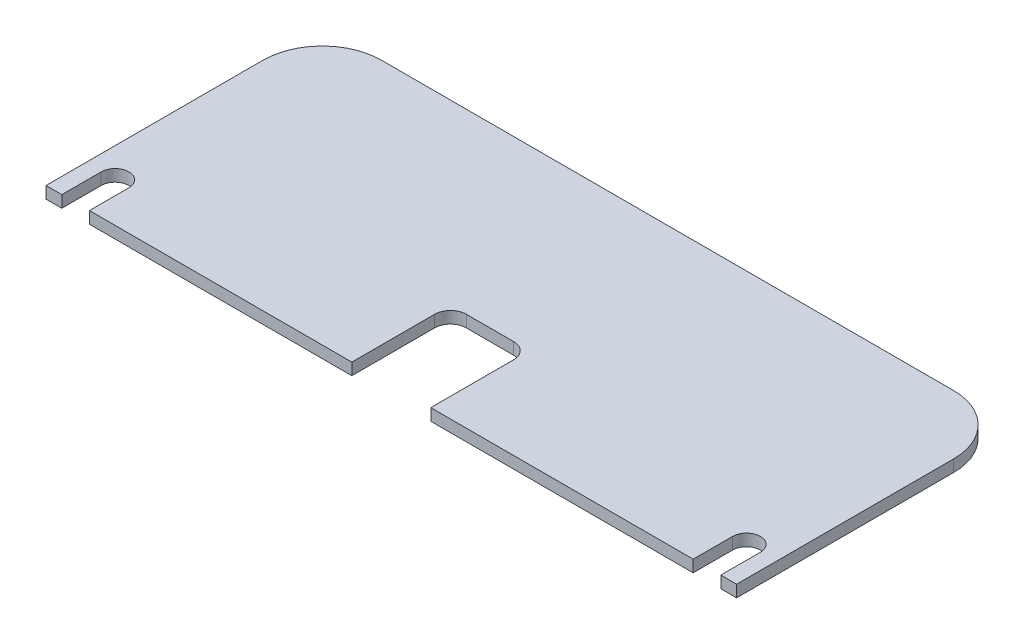
SolidWorks part; units mm, degrees
ref_plane "Front Plane" through (0, 0, 0) normal (0, 0, 1) x (1, 0, 0)
ref_plane "Top Plane" through (0, 0, 0) normal (0, 1, 0) x (1, 0, 0)
ref_plane "Right Plane" through (0, 0, 0) normal (1, 0, 0) x (0, 0, -1)
sketch "Sketch1" plane through (0, 0, 0) normal (0, 1, 0) x (1, 0, 0)
  line L1 (0, 0) -> (175, 0)
  line L2 (0, 0) -> (0, 70)
  line L3 (0, 70) -> (175, 70)
  line L4 (175, 0) -> (175, 70)
  dimension "D1" = 175
  dimension "D2" = 70
extrude "Boss-Extrude1" add sketch "Sketch1" along normal blind 3
sketch "Sketch2" plane through (0, 3, 0) normal (0, 1, 0) x (1, 0, 0)
  line L0 (87.5, 70) -> (87.5, 0) construction
  line L1 (77.5, 25) -> (97.5, 25)
  line L2 (77.5, 25) -> (77.5, 0)
  line L3 (77.5, 0) -> (97.5, 0)
  line L4 (97.5, 25) -> (97.5, 0)
  line L5 (0, 0) -> (175, 0) construction
  line L6 (175, 70) -> (0, 70) construction
  line L7 (11, 10) -> (11, 0)
  line L8 (11, 0) -> (4, 0)
  line L9 (4, 0) -> (4, 10)
  line L10 (171, 0) -> (171, 10)
  line L11 (164, 0) -> (171, 0)
  line L12 (164, 10) -> (164, 0)
  circle A0 centre (7.5, 10) radius 3.5 construction
  arc A2 (4, 10) -> (11, 10) centre (7.5, 10) cw
  circle A3 centre (167.5, 10) radius 3.5 construction
  arc A4 (171, 10) -> (164, 10) centre (167.5, 10) ccw
  point P14 (87.5, 70)
  dimension "D3" = 7
  dimension "D1" = 20
  dimension "D2" = 10
  dimension "D4" = 80
  dimension "D5" = 25
  dimension "D6" = 10
extrude "Cut-Extrude1" cut sketch "Sketch2" against normal blind 5
fillet "Fillet1" radius 4 2 edges at (97.5, 1.5, -25) (77.5, 1.5, -25)
fillet "Fillet2" radius 15 2 edges at (175, 1.5, -70) (0, 1.5, -70)
